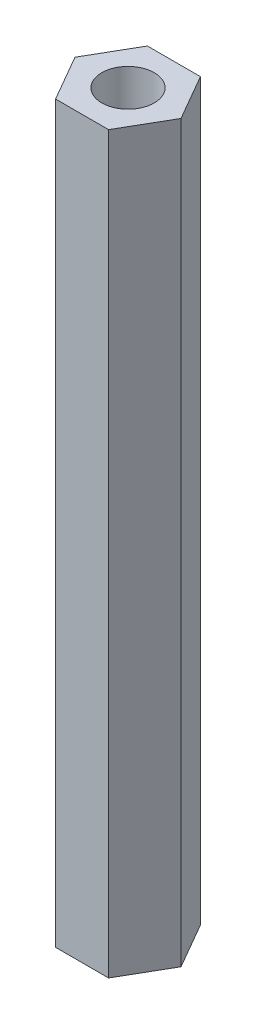
SolidWorks part; units mm, degrees
ref_plane "Front Plane" through (0, 0, 0) normal (0, 0, 1) x (1, 0, 0)
ref_plane "Top Plane" through (0, 0, 0) normal (0, 1, 0) x (1, 0, 0)
ref_plane "Right Plane" through (0, 0, 0) normal (1, 0, 0) x (0, 0, -1)
sketch "Sketch1" plane through (0, 0, 0) normal (0, 1, 0) x (1, 0, 0)
  line L1 (2.0207, 3.5) -> (-2.0207, 3.5)
  line L2 (-2.0207, 3.5) -> (-4.0415, 0)
  line L3 (-4.0415, 0) -> (-2.0207, -3.5)
  line L4 (-2.0207, -3.5) -> (2.0207, -3.5)
  line L5 (2.0207, -3.5) -> (4.0415, 0)
  line L6 (4.0415, 0) -> (2.0207, 3.5)
  circle A0 centre (0, 0) radius 3.5 construction
  circle A1 centre (0, 0) radius 2
  dimension "D1" = 7
  dimension "D2" = 4
extrude "Boss-Extrude1" add sketch "Sketch1" along normal blind 56
